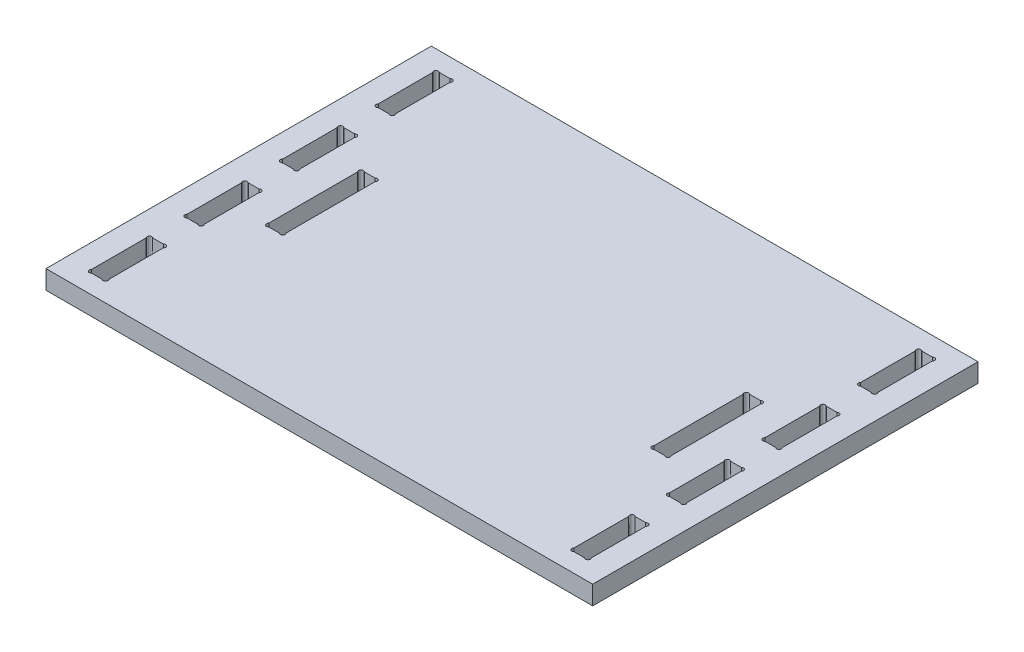
SolidWorks part; units mm, degrees
ref_plane "Alzado" through (0, 0, 0) normal (0, 0, 1) x (1, 0, 0)
ref_plane "Planta" through (0, 0, 0) normal (0, 1, 0) x (1, 0, 0)
ref_plane "Vista lateral" through (0, 0, 0) normal (1, 0, 0) x (0, 0, -1)
sketch "Croquis1" plane through (0, 0, 0) normal (0, 1, 0) x (1, 0, 0)
  line L0 (0, 0) -> (349.0036, 0)
  line L1 (0, 0) -> (0, -246)
  line L2 (0, -246) -> (349.0036, -246)
  line L3 (349.0036, 0) -> (349.0036, -246)
  line L4 (17.1213, -173) -> (23.8787, -173)
  line L5 (15, -170.8787) -> (15, -136.1213)
  line L6 (26, -170.8787) -> (26, -136.1213)
  line L7 (23.8787, -134) -> (17.1213, -134)
  line L8 (46, -149.7574) -> (46, -93.0581)
  line L9 (17.1213, -112) -> (23.8787, -112)
  line L10 (15, -109.8787) -> (15, -75.1213)
  line L11 (17.1213, -73) -> (23.8787, -73)
  line L12 (26, -109.8787) -> (26, -75.1213)
  line L13 (26, -231.8787) -> (26, -197.1213)
  line L14 (17.1213, -51) -> (23.8787, -51)
  line L15 (15, -231.8787) -> (15, -197.1213)
  line L16 (15, -48.8787) -> (15, -14.1213)
  line L17 (17.1213, -12) -> (23.8787, -12)
  line L19 (331.8822, -234) -> (325.1249, -234)
  line L20 (23.8787, -195) -> (17.1213, -195)
  line L21 (334.0036, -231.8787) -> (334.0036, -197.1213)
  line L22 (17.1213, -234) -> (23.8787, -234)
  line L23 (331.8822, -195) -> (325.1249, -195)
  line L24 (26, -14.1213) -> (26, -48.8787)
  line L25 (325.1249, -173) -> (331.8822, -173)
  line L26 (323.0036, -170.8787) -> (323.0036, -136.1213)
  line L27 (325.1249, -134) -> (331.8822, -134)
  line L28 (334.0036, -170.8787) -> (334.0036, -136.1213)
  line L29 (325.1249, -112) -> (331.8822, -112)
  line L30 (323.0036, -109.8787) -> (323.0036, -75.1213)
  line L31 (325.1249, -73) -> (331.8822, -73)
  line L32 (334.0036, -109.8787) -> (334.0036, -75.1213)
  line L33 (325.1249, -51) -> (331.8822, -51)
  line L34 (323.0036, -48.8787) -> (323.0036, -14.1213)
  line L35 (325.1249, -12) -> (331.8822, -12)
  line L36 (334.0036, -48.8787) -> (334.0036, -14.1213)
  line L37 (48.1213, -151.8787) -> (54.8787, -151.8787)
  line L38 (57, -149.7574) -> (57, -93)
  line L39 (54.8787, -90.8787) -> (48.0616, -90.8787)
  line L41 (303.0036, -149.7574) -> (303.0036, -93)
  line L42 (300.8822, -151.8787) -> (294.1249, -151.8787)
  line L43 (292.0036, -149.7574) -> (292.0036, -93)
  line L64 (323.0036, -231.8787) -> (323.0036, -197.1213)
  line L65 (294.1249, -90.8787) -> (300.8822, -90.8787)
  arc A0 (15, -231.8787) -> (17.1213, -234) centre (16.0607, -232.9393) ccw
  arc A1 (23.8787, -234) -> (26, -231.8787) centre (24.9393, -232.9393) ccw
  arc A2 (26, -197.1213) -> (23.8787, -195) centre (24.9393, -196.0607) ccw
  arc A3 (17.1213, -195) -> (15, -197.1213) centre (16.0607, -196.0607) ccw
  arc A4 (15, -170.8787) -> (17.1213, -173) centre (16.0607, -171.9393) ccw
  arc A5 (23.8787, -173) -> (26, -170.8787) centre (24.9393, -171.9393) ccw
  arc A6 (17.1213, -134) -> (15, -136.1213) centre (16.0607, -135.0607) ccw
  arc A7 (26, -136.1213) -> (23.8787, -134) centre (24.9393, -135.0607) ccw
  arc A8 (15, -109.8787) -> (17.1213, -112) centre (16.0607, -110.9393) ccw
  arc A9 (23.8787, -112) -> (26, -109.8787) centre (24.9393, -110.9393) ccw
  arc A10 (17.1213, -73) -> (15, -75.1213) centre (16.0607, -74.0607) ccw
  arc A11 (26, -75.1213) -> (23.8787, -73) centre (24.9393, -74.0607) ccw
  arc A12 (15, -48.8787) -> (17.1213, -51) centre (16.0607, -49.9393) ccw
  arc A13 (23.8787, -51) -> (26, -48.8787) centre (24.9393, -49.9393) ccw
  arc A14 (17.1213, -12) -> (15, -14.1213) centre (16.0607, -13.0607) ccw
  arc A15 (26, -14.1213) -> (23.8787, -12) centre (24.9393, -13.0607) ccw
  arc A16 (292.0036, -149.7574) -> (294.1249, -151.8787) centre (293.0642, -150.818) ccw
  arc A17 (300.8822, -151.8787) -> (303.0036, -149.7574) centre (301.9429, -150.818) ccw
  arc A18 (294.1249, -90.8787) -> (292.0036, -93) centre (293.0642, -91.9393) ccw
  arc A19 (303.0036, -93) -> (300.8822, -90.8787) centre (301.9429, -91.9393) ccw
  arc A20 (323.0036, -48.8787) -> (325.1249, -51) centre (324.0642, -49.9393) ccw
  arc A21 (331.8822, -51) -> (334.0036, -48.8787) centre (332.9429, -49.9393) ccw
  arc A22 (325.1249, -12) -> (323.0036, -14.1213) centre (324.0642, -13.0607) ccw
  arc A23 (334.0036, -14.1213) -> (331.8822, -12) centre (332.9429, -13.0607) ccw
  arc A24 (325.1249, -73) -> (323.0036, -75.1213) centre (324.0642, -74.0607) ccw
  arc A25 (334.0036, -75.1213) -> (331.8822, -73) centre (332.9429, -74.0607) ccw
  arc A26 (323.0036, -109.8787) -> (325.1249, -112) centre (324.0642, -110.9393) ccw
  arc A27 (331.8822, -112) -> (334.0036, -109.8787) centre (332.9429, -110.9393) ccw
  arc A28 (323.0036, -170.8787) -> (325.1249, -173) centre (324.0642, -171.9393) ccw
  arc A29 (331.8822, -173) -> (334.0036, -170.8787) centre (332.9429, -171.9393) ccw
  arc A30 (325.1249, -134) -> (323.0036, -136.1213) centre (324.0642, -135.0607) ccw
  arc A31 (334.0036, -136.1213) -> (331.8822, -134) centre (332.9429, -135.0607) ccw
  arc A32 (48.0616, -90.8787) -> (46, -93.0581) centre (47.0308, -91.9684) ccw
  arc A33 (57, -93) -> (54.8787, -90.8787) centre (55.9393, -91.9393) ccw
  arc A34 (46, -149.7574) -> (48.1213, -151.8787) centre (47.0607, -150.818) ccw
  arc A35 (54.8787, -151.8787) -> (57, -149.7574) centre (55.9393, -150.818) ccw
  arc A36 (323.0036, -231.8787) -> (325.1249, -234) centre (324.0642, -232.9393) ccw
  arc A37 (331.8822, -234) -> (334.0036, -231.8787) centre (332.9429, -232.9393) ccw
  arc A38 (325.1249, -195) -> (323.0036, -197.1213) centre (324.0642, -196.0607) ccw
  arc A39 (334.0036, -197.1213) -> (331.8822, -195) centre (332.9429, -196.0607) ccw
  dimension "D7" = 12
  dimension "D6" = 15
  dimension "D2" = 22
  dimension "D1" = 22
  dimension "D10" = 20
  dimension "D3" = 22
  dimension "D4" = 15
  dimension "D5" = 12
  dimension "D8" = 12
  dimension "D9" = 20
extrude "Saliente-Extruir1" add sketch "Croquis1" along normal blind 12
